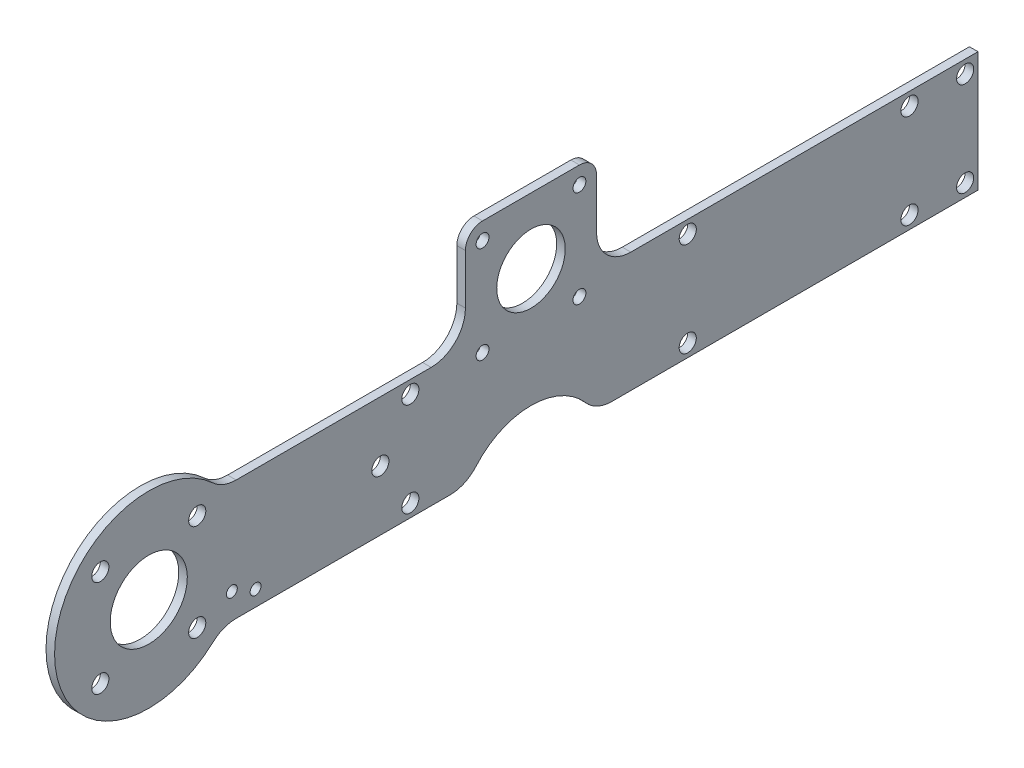
SolidWorks part; units mm, degrees
ref_plane "Front Plane" through (0, 0, 0) normal (0, 0, 1) x (1, 0, 0)
ref_plane "Top Plane" through (0, 0, 0) normal (0, 1, 0) x (1, 0, 0)
ref_plane "Right Plane" through (0, 0, 0) normal (1, 0, 0) x (0, 0, -1)
sketch "Sketch1" plane through (-38.8871, 0, 0) normal (-1, 0, 0) x (0, 0, 1)
  line L0 (210.2517, 740.5311) -> (406.4, 740.5311)
  line L2 (406.4, 784.9811) -> (210.2517, 784.9811)
  line L3 (415.925, 740.5311) -> (475.7483, 740.5311)
  line L4 (200.7267, 784.9811) -> (200.7267, 740.5311)
  line L5 (200.7267, 740.5311) -> (210.2517, 740.5311)
  line L6 (210.2517, 740.5311) -> (210.2517, 784.9811)
  line L7 (210.2517, 784.9811) -> (200.7267, 784.9811)
  line L8 (200.7267, 784.9811) -> (200.7267, 740.5311)
  line L9 (200.7267, 740.5311) -> (210.2517, 740.5311)
  line L10 (210.2517, 740.5311) -> (210.2517, 784.9811) construction
  line L11 (210.2517, 784.9811) -> (200.7267, 784.9811)
  line L12 (200.7267, 762.7561) -> (508.1271, 762.7561) construction
  line L13 (415.925, 784.9811) -> (475.7483, 784.9811)
  line L14 (508.1271, 762.7561) -> (366.438, 798.1792) construction
  line L15 (406.4, 784.9811) -> (406.4, 740.5311)
  line L16 (406.4, 740.5311) -> (415.925, 740.5311)
  line L17 (415.925, 740.5311) -> (415.925, 784.9811)
  line L18 (415.925, 784.9811) -> (406.4, 784.9811)
  line L19 (406.4, 784.9811) -> (406.4, 740.5311) construction
  line L20 (406.4, 740.5311) -> (415.925, 740.5311)
  line L21 (415.925, 740.5311) -> (415.925, 784.9811) construction
  line L22 (415.925, 784.9811) -> (406.4, 784.9811)
  line L23 (205.4892, 780.2186) -> (411.1625, 780.2186) construction
  line L24 (308.3258, 784.9811) -> (308.3258, 740.5311) construction
  line L25 (428.625, 772.2811) -> (-111.0742, 772.2811) construction
  line L26 (508.1271, 762.7561) -> (490.1666, 780.7167) construction
  line L27 (384.3985, 816.1397) -> (348.4775, 816.1397) construction
  line L28 (384.3985, 816.1397) -> (384.3985, 780.2186) construction
  line L29 (384.3985, 780.2186) -> (348.4775, 780.2186) construction
  line L30 (348.4775, 816.1397) -> (348.4775, 780.2186) construction
  line L31 (384.3985, 816.1397) -> (348.4775, 780.2186) construction
  line L32 (384.3985, 780.2186) -> (348.4775, 816.1397) construction
  line L33 (428.625, 772.2811) -> (-111.0742, 772.2811) construction
  line L34 (390.7485, 773.8686) -> (342.1275, 773.8686)
  line L35 (366.438, 798.1792) -> (366.438, 780.2186) construction
  line L36 (342.1275, 822.4897) -> (342.1275, 784.9811)
  line L37 (390.7485, 822.4897) -> (342.1275, 822.4897)
  line L38 (390.7485, 822.4897) -> (390.7485, 784.9811)
  line L39 (390.7485, 784.9811) -> (390.7485, 773.8686)
  line L40 (342.1275, 784.9811) -> (342.1275, 773.8686)
  line L41 (342.1275, 822.4897) -> (342.1275, 773.8686) construction
  line L43 (390.7485, 822.4897) -> (390.7485, 773.8686) construction
  circle A0 centre (205.4892, 780.2186) radius 2.6035 construction
  circle A1 centre (205.4892, 745.2936) radius 2.6035 construction
  circle A2 centre (205.4892, 780.2186) radius 2.6035 construction
  circle A3 centre (205.4892, 745.2936) radius 2.6035 construction
  circle A4 centre (205.4892, 780.2186) radius 3.175
  circle A5 centre (205.4892, 745.2936) radius 3.175
  circle A6 centre (411.1625, 745.2936) radius 2.6035 construction
  circle A7 centre (411.1625, 780.2186) radius 2.6035 construction
  circle A8 centre (411.1625, 745.2936) radius 2.6035 construction
  circle A9 centre (411.1625, 780.2186) radius 2.6035 construction
  circle A10 centre (411.1625, 780.2186) radius 3.175
  circle A11 centre (411.1625, 745.2936) radius 3.175
  arc A12 (484.3827, 737.1445) -> (484.3827, 788.3678) centre (508.1271, 762.7561) ccw
  circle A13 centre (17.316, 762.7561) radius 3.175 construction
  circle A14 centre (17.316, 762.7561) radius 3.175 construction
  circle A17 centre (508.1271, 762.7561) radius 14.2875
  circle A18 centre (490.1666, 780.7167) radius 3.175
  circle A19 centre (526.0876, 780.7167) radius 3.175
  circle A20 centre (526.0876, 744.7956) radius 3.175
  circle A21 centre (490.1666, 744.7956) radius 3.175
  circle A23 centre (308.3258, 780.2186) radius 3.175
  circle A24 centre (308.3258, 745.2936) radius 3.175
  circle A25 centre (226.1267, 780.2186) radius 3.175
  circle A26 centre (226.1267, 745.2936) radius 3.175
  arc A32 (484.3827, 737.1445) -> (475.7483, 740.5311) centre (475.7483, 727.8311) ccw
  arc A33 (484.3827, 788.3678) -> (475.7483, 784.9811) centre (475.7483, 797.6811) cw
  circle A34 centre (366.438, 798.1792) radius 12.7
  circle A35 centre (384.3985, 780.2186) radius 2.3813
  circle A36 centre (348.4775, 780.2186) radius 2.3813
  circle A37 centre (348.4775, 816.1397) radius 2.3813
  circle A38 centre (384.3985, 816.1397) radius 2.3813
  circle A39 centre (366.438, 798.1792) radius 25 construction
  circle A40 centre (366.438, 798.1792) radius 25 construction
  arc A41 (345.2056, 740.5311) -> (387.6703, 740.5311) centre (366.438, 727.3331) cw construction
  arc A42 (342.9925, 740.5311) -> (389.8835, 740.5311) centre (366.438, 727.3331) cw
  circle A43 centre (422.275, 762.7561) radius 3.175
  circle A44 centre (366.438, 727.3331) radius 26.905 construction
  circle A45 centre (366.438, 727.3331) radius 25 construction
  circle A46 centre (477.3273, 749.9984) radius 2.0193 construction
  circle A47 centre (468.5273, 746.3534) radius 2.0193 construction
  circle A48 centre (477.3273, 749.9984) radius 2.0193
  circle A49 centre (468.5273, 746.3534) radius 2.0193
  point P35 (481.1863, 784.9811)
  point P36 (481.1863, 740.5311)
  point P38 (481.1863, 740.5311)
  point P49 (508.1271, 762.7561)
  point P63 (481.1863, 784.9811)
  point P65 (382.6262, 828.15)
  point P79 (366.438, 798.1792)
  point P95 (374.6581, 718.7427)
  point P96 (377.6555, 726.052)
  dimension "D2" = 6.35
  dimension "D5" = 34.925
  dimension "D6" = 12.7
  dimension "D7" = 28.575
  dimension "D9" = 6.35
  dimension "D11" = 6.35
  dimension "D15" = 4.7625
  dimension "D19" = 1.905
  dimension "D20" = 25.4
  dimension "D21" = 6.35
  dimension "D3" = 0
  dimension "D4" = 490.8112
  dimension "D8" = 45
  dimension "D10" = 25.4
  dimension "D12" = 15.875
  dimension "D13" = 146.05
  dimension "D14" = 50.8
  dimension "D17" = 7.9375
  dimension "D22" = 6.35
  dimension "D1" = 0
  dimension "D18" = 6.35
  dimension "D16" = 4
extrude "Boss-Extrude1" add sketch "Sketch1" along normal blind 3.175
fillet "Fillet1" radius 12.7 4 edges at (-40.4746, 784.9811, 390.7485) (-40.4746, 784.9811, 342.1275) (-40.4746, 740.5311, 389.8835) (-40.4746, 740.5311, 342.9925)
fillet "Fillet2" radius 6.35 2 edges at (-40.4746, 822.4897, 342.1275) (-40.4746, 822.4897, 390.7485)
